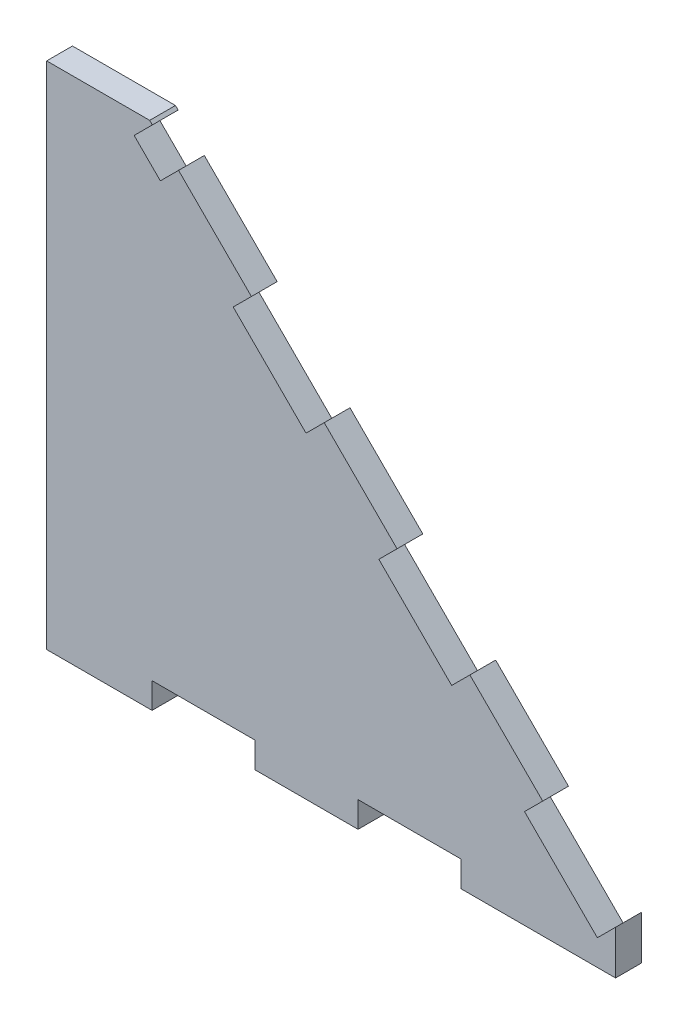
SolidWorks part; units mm, degrees
material "Acrylic (Medium-high impact)"
ref_plane "Front Plane" through (0, 0, 0) normal (0, 0, 1) x (1, 0, 0)
ref_plane "Top Plane" through (0, 0, 0) normal (0, 1, 0) x (1, 0, 0)
ref_plane "Right Plane" through (0, 0, 0) normal (1, 0, 0) x (0, 0, -1)
sketch "Sketch2" plane through (0, 0, 0) normal (0, 0, 1) x (1, 0, 0)
  line L0 (12.7, 62.8618) -> (70.1417, 5.4201)
  line L1 (0, 0) -> (127, 0)
  line L2 (0, 0) -> (0, 62.8618)
  line L3 (0, 62.8618) -> (127, 62.8618)
  line L4 (127, 0) -> (127, 62.8618)
  line L13 (70.1417, 5.4201) -> (70.1417, 0)
  line L14 (61.1615, 14.4003) -> (70.1417, 5.4201)
  line L15 (61.1615, 14.4003) -> (58.9164, 12.1553)
  line L16 (70.1417, 5.4201) -> (67.8967, 3.175)
  line L17 (58.9164, 12.1553) -> (67.8967, 3.175)
  line L18 (70.1417, 5.4201) -> (88.975, -13.4132) construction
  line L19 (43.201, 32.3608) -> (52.1812, 23.3806)
  line L20 (43.201, 32.3608) -> (40.9559, 30.1158)
  line L21 (40.9559, 30.1158) -> (49.9362, 21.1355)
  line L22 (52.1812, 23.3806) -> (49.9362, 21.1355)
  line L23 (25.2404, 50.3213) -> (34.2207, 41.3411)
  line L24 (25.2404, 50.3213) -> (22.9954, 48.0763)
  line L25 (22.9954, 48.0763) -> (31.9756, 39.096)
  line L26 (34.2207, 41.3411) -> (31.9756, 39.096)
  line L27 (13.0273, 62.5345) -> (16.2602, 59.3016)
  line L28 (13.0273, 62.5345) -> (10.7822, 60.2894)
  line L29 (16.2602, 59.3016) -> (14.0151, 57.0565)
  line L30 (10.7822, 60.2894) -> (14.0151, 57.0565)
  dimension "D1" = 62.8618
  dimension "D2" = 3.175
  dimension "D3" = 12.7
  dimension "D4" = 45
  dimension "D5" = 3.175
  dimension "D6" = 12.7
  dimension "D8" = 12.7
  dimension "D9" = 12.7
  dimension "D10" = 4.572
  dimension "D11" = 127
  dimension "D7" = 3
extrude "Boss-Extrude1" add sketch "Sketch2" along normal blind 3.175 contours L30 L28 L0 L3 L2 L1 L13 L16 L17 L15 L22 L21 L20 L26 L25 L24 L29
sketch "Sketch3" plane through (0, 0, 3.175) normal (0, 0, 1) x (1, 0, 0)
  line L0 (0, 0) -> (70.1417, 0) construction
  line L1 (38.3917, 0) -> (51.0917, 0)
  line L2 (38.3917, 0) -> (38.3917, 3.175)
  line L3 (38.3917, 3.175) -> (51.0917, 3.175)
  line L4 (51.0917, 0) -> (51.0917, 3.175)
  line L5 (70.1417, 5.4201) -> (70.1417, 0) construction
  line L7 (12.9917, 0) -> (25.6917, 0)
  line L8 (12.9917, 0) -> (12.9917, 3.175)
  line L9 (12.9917, 3.175) -> (25.6917, 3.175)
  line L10 (25.6917, 0) -> (25.6917, 3.175)
  dimension "D1" = 3.175
  dimension "D2" = 19.05
  dimension "D3" = 12.7
  dimension "D4" = 12.7
  dimension "D5" = 12.7
extrude "Cut-Extrude1" cut sketch "Sketch3" against normal through all and the other way through all
